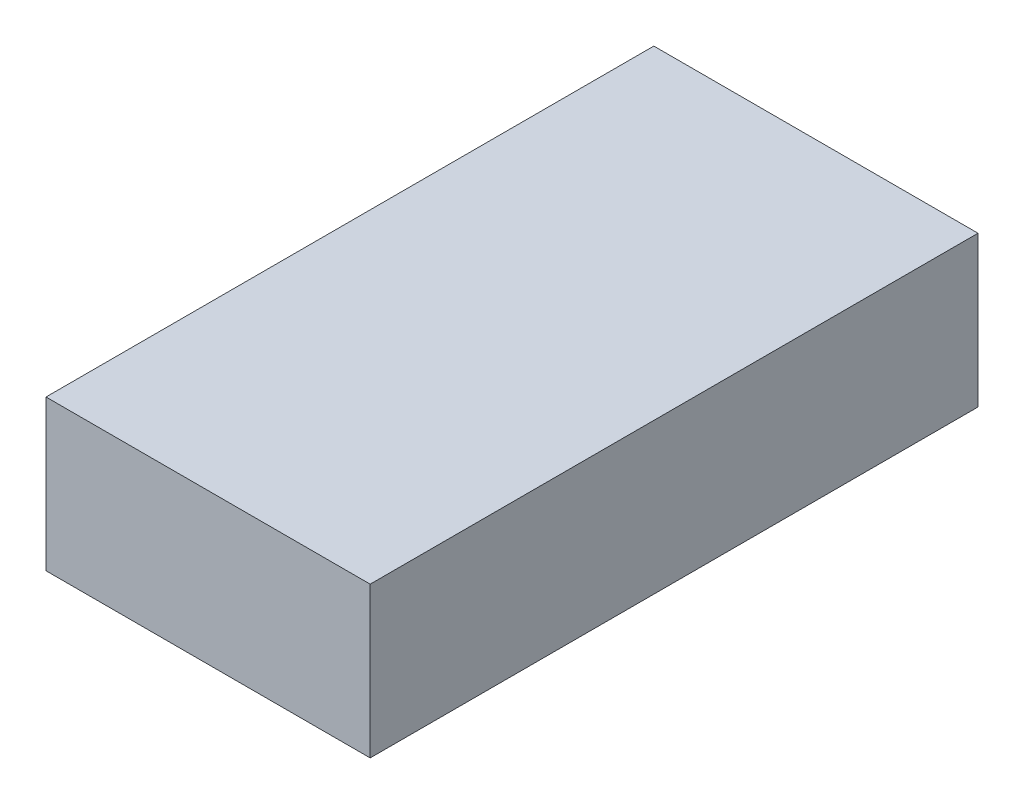
SolidWorks part; units mm, degrees
ref_plane "Ön Düzlem" through (0, 0, 0) normal (0, 0, 1) x (1, 0, 0)
ref_plane "Üst Düzlem" through (0, 0, 0) normal (0, 1, 0) x (1, 0, 0)
ref_plane "Sağ Düzlem" through (0, 0, 0) normal (1, 0, 0) x (0, 0, -1)
sketch "Çizim1" plane through (0, 0, 0) normal (0, 0, 1) x (1, 0, 0)
  line L1 (-28, 13) -> (28, 13)
  line L2 (-28, 13) -> (-28, -13)
  line L3 (-28, -13) -> (28, -13)
  line L4 (28, 13) -> (28, -13)
  dimension "D1" = 56
  dimension "D2" = 26
  dimension "D3" = 13
  dimension "D4" = 28
extrude "Yükseklik-Ekstrüzyon1" add sketch "Çizim1" along normal blind 105
